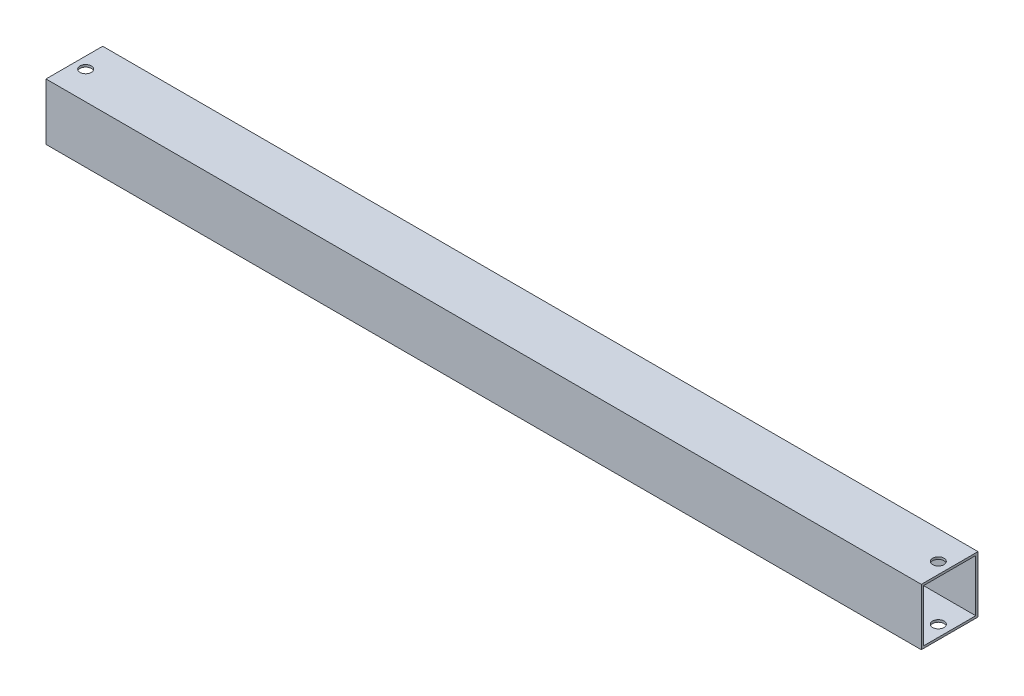
SolidWorks part; units mm, degrees
ref_plane "Front Plane" through (0, 0, 0) normal (0, 0, 1) x (1, 0, 0)
ref_plane "Top Plane" through (0, 0, 0) normal (0, 1, 0) x (1, 0, 0)
ref_plane "Right Plane" through (0, 0, 0) normal (1, 0, 0) x (0, 0, -1)
sketch "Sketch1" plane through (0, 0, 0) normal (1, 0, 0) x (0, 0, -1)
  line L0 (-11.5, -11.5) -> (11.5, -11.5)
  line L1 (-12.5, -12.5) -> (12.5, -12.5)
  line L2 (-12.5, -12.5) -> (-12.5, 12.5)
  line L3 (-12.5, 12.5) -> (12.5, 12.5)
  line L4 (12.5, -12.5) -> (12.5, 12.5)
  line L5 (-12.5, -12.5) -> (12.5, 12.5) construction
  line L6 (-12.5, 12.5) -> (12.5, -12.5) construction
  line L7 (11.5, -11.5) -> (11.5, 11.5)
  line L8 (-11.5, 11.5) -> (11.5, 11.5)
  line L9 (-11.5, -11.5) -> (-11.5, 11.5)
  point P0 (0, 0)
  dimension "D1" = 25
  dimension "D2" = 25
  dimension "D3" = 1
extrude "Boss-Extrude1" add sketch "Sketch1" along normal blind 386
sketch "Sketch2" plane through (0, 12.5, 0) normal (0, 1, 0) x (1, 0, 0)
  line L0 (0, 0) -> (386, 0) construction
  line L1 (386, 12.5) -> (386, -12.5) construction
  line L2 (0, 12.5) -> (0, -12.5) construction
  circle A0 centre (5, 0) radius 2.5
  circle A1 centre (381, 0) radius 2.5
  dimension "D1" = 5
  dimension "D3" = 5
  dimension "D2" = 5
extrude "Cut-Extrude1" cut sketch "Sketch2" against normal through all
